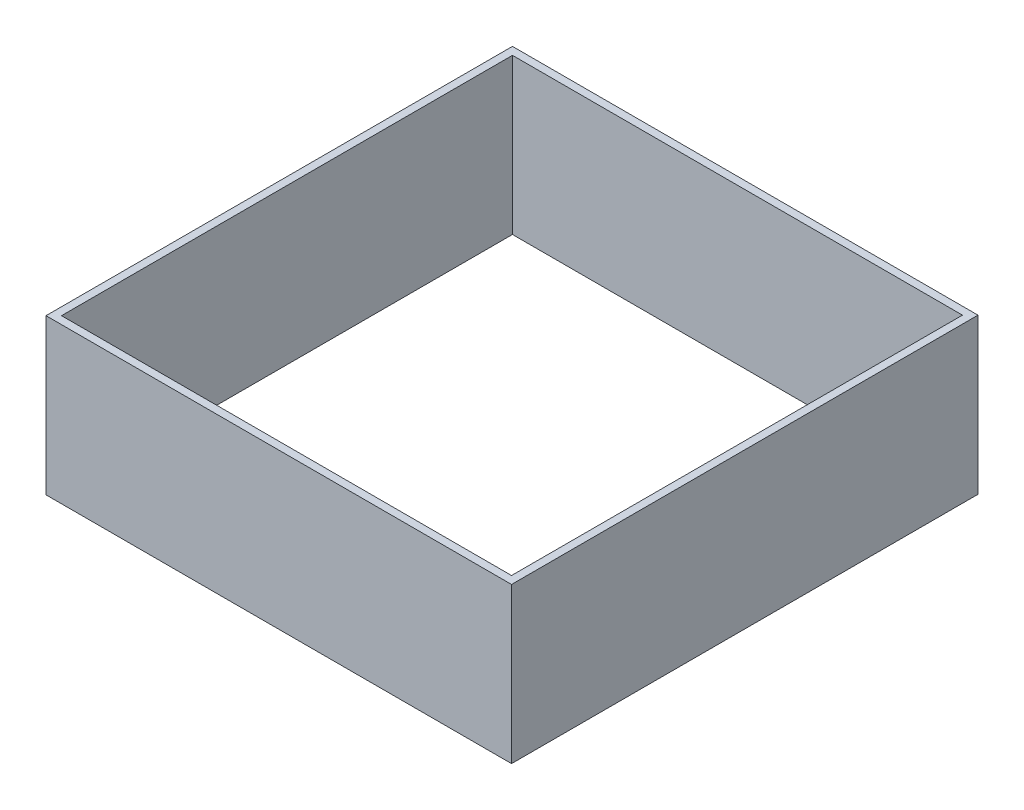
SolidWorks part; units mm, degrees
material "Aleación 1060"
ref_plane "Alzado" through (0, 0, 0) normal (0, 0, 1) x (1, 0, 0)
ref_plane "Planta" through (0, 0, 0) normal (0, 1, 0) x (1, 0, 0)
ref_plane "Vista lateral" through (0, 0, 0) normal (1, 0, 0) x (0, 0, -1)
sketch "Croquis1" plane through (0, 0, 0) normal (0, 0, 1) x (1, 0, 0)
  line L1 (-20, 20) -> (20, 20)
  line L2 (-20, 20) -> (-20, -20)
  line L3 (-20, -20) -> (20, -20)
  line L4 (20, 20) -> (20, -20)
  line L5 (-20, 20) -> (20, -20) construction
  line L6 (-20, -20) -> (20, 20) construction
  point P0 (0, 0)
  dimension "D1" = 40
  dimension "D2" = 40
extrude "Saliente-Extruir1" add sketch "Croquis1" along normal blind 0.3 contours L1 L4 L3 L2
sketch "Croquis2" plane through (0, 0, 0) normal (0, 1, 0) x (1, 0, 0)
  line L0 (0, 0) -> (0, 10) construction
  line L1 (-20, 0) -> (20, 0) construction
  line L2 (-5, 10) -> (-5, 0)
  line L3 (5, 10) -> (5, 0)
  line L4 (-5, 0) -> (5, 0)
  circle A0 centre (0, 10) radius 2.5
  arc A1 (5, 10) -> (-5, 10) centre (0, 10) ccw
  dimension "D2" = 5
  dimension "D3" = 10
  dimension "D1" = 10
extrude "Saliente-Extruir2" add sketch "Croquis2" along normal blind 10 and the other way blind 10
sketch "Croquis3" plane through (0, 0, 0) normal (0, 1, 0) x (1, 0, 0)
  line L1 (-7.0281, 16) -> (7.0281, 16)
  line L2 (-7.0281, 16) -> (-7.0281, 4)
  line L3 (-7.0281, 4) -> (7.0281, 4)
  line L4 (7.0281, 16) -> (7.0281, 4)
  line L5 (-7.0281, 16) -> (7.0281, 4) construction
  line L6 (-7.0281, 4) -> (7.0281, 16) construction
  line L7 (-20, 0) -> (20, 0) construction
  point P0 (0, 10)
  dimension "D1" = 4
extrude "Cortar-Extruir1" cut sketch "Croquis3" against normal blind 2.5 and the other way blind 2.5
sketch "Croquis4" plane through (0, 0, 0.3) normal (0, 0, 1) x (1, 0, 0)
  line L1 (-150, 50) -> (150, 50)
  line L2 (-150, 50) -> (-150, -50)
  line L3 (-150, -50) -> (150, -50)
  line L4 (150, 50) -> (150, -50)
  line L5 (-150, 50) -> (150, -50) construction
  line L6 (-150, -50) -> (150, 50) construction
  point P0 (0, 0)
  dimension "D1" = 100
  dimension "D2" = 300
extrude "Saliente-Extruir3" add sketch "Croquis4" along normal blind 5
sketch "Croquis5" plane through (150, 0, 0) normal (1, 0, 0) x (0, 0, -1)
  line L1 (-5.3, 50) -> (294.7, 50)
  line L2 (-5.3, 50) -> (-5.3, -50)
  line L3 (-5.3, -50) -> (294.7, -50)
  line L4 (294.7, 50) -> (294.7, -50)
  dimension "D1" = 300
extrude "Saliente-Extruir4" add sketch "Croquis5" against normal blind 5 contours L1 L4 L3 L2
mirror "Simetría2" about plane through (0, 0, 0) normal (1, 0, 0) of "Saliente-Extruir4"
ref_plane "Plano1" through (0, 0, 5) normal (0, 0, 1) x (1, 0, 0)
ref_plane "Plano2" through (0, 0, -145) normal (0, 0, 1) x (1, 0, 0)
mirror "Simetría3" about plane through (0, 0, -145) normal (0, 0, 1) of "Saliente-Extruir3"
ref_plane "Plano4" through (0, -50, 0) normal (0, 1, 0) x (1, 0, 0)
sketch "Croquis7" plane through (0, -50, 0) normal (0, 1, 0) x (1, 0, 0)
  line L0 (-145, -0.3) -> (-145, 290.3) construction
  line L1 (-145, 0) -> (145, 0)
  line L2 (-145, 0) -> (-145, 290.3)
  line L3 (-145, 290.3) -> (145, 290.3)
  line L4 (145, 0) -> (145, 290.3)
